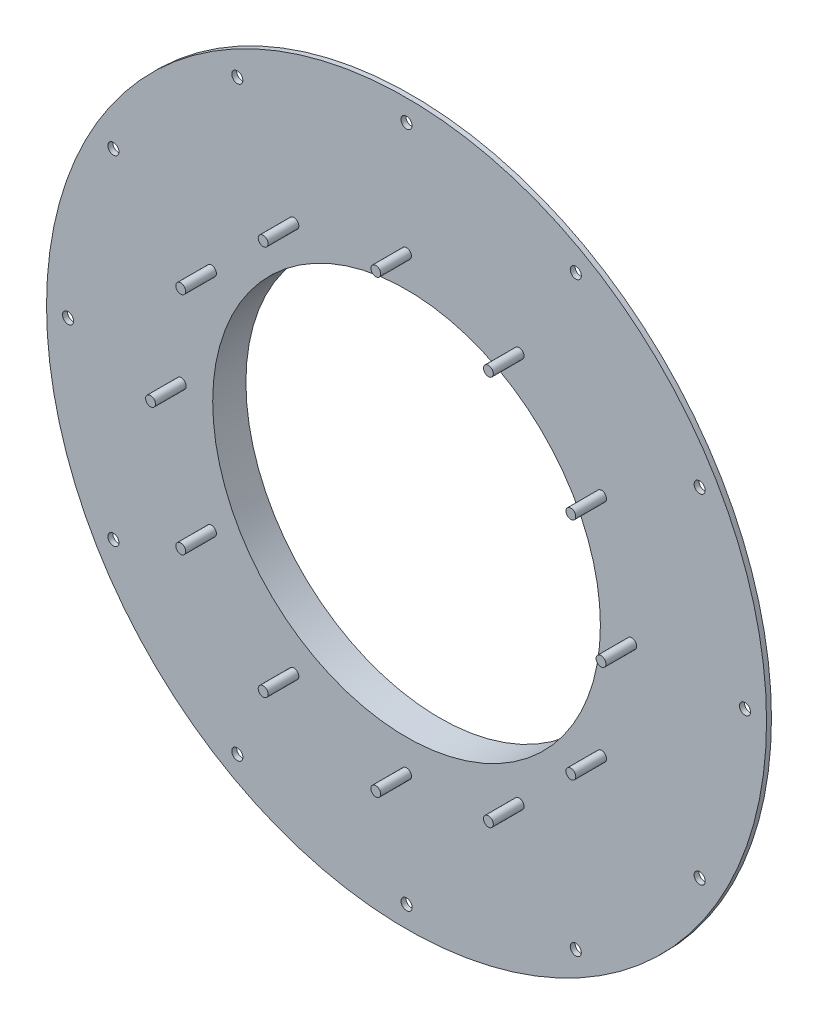
SolidWorks part; units mm, degrees
material "ASTM A36 Steel"
ref_plane "Front Plane" through (0, 0, 0) normal (0, 0, 1) x (1, 0, 0)
ref_plane "Top Plane" through (0, 0, 0) normal (0, 1, 0) x (1, 0, 0)
ref_plane "Right Plane" through (0, 0, 0) normal (1, 0, 0) x (0, 0, -1)
sketch "Sketch1" plane through (0, 0, 0) normal (0, 0, 1) x (1, 0, 0)
  circle A0 centre (0, 0) radius 292.5
  circle A1 centre (0, 0) radius 157.5
  dimension "D1" = 585
  dimension "D2" = 315
extrude "Boss-Extrude1" add sketch "Sketch1" along normal blind 4
sketch "Sketch2" plane through (0, 0, 4) normal (0, 0, 1) x (1, 0, 0)
  circle A0 centre (0, 275) radius 4.5
  dimension "D1" = 9
  dimension "D2" = 275
extrude "Cut-Extrude1" cut sketch "Sketch2" against normal through all
pattern_circular "CirPattern1" count 12 every 30 about axis through (0, 0, 0) along (0, 0, 1) of "Cut-Extrude1"
sketch "Sketch3" plane through (0, 0, 4) normal (0, 0, 1) x (1, 0, 0)
  circle A0 centre (0, 183) radius 4
  dimension "D1" = 8
  dimension "D2" = 183
extrude "Boss-Extrude2" add sketch "Sketch3" along normal blind 25
pattern_circular "CirPattern2" count 12 every 30 about axis through (0, 0, 0) along (0, 0, 1) of "Boss-Extrude2"
sketch "Sketch4" plane through (0, 0, 0) normal (0, 0, -1) x (-1, 0, 0)
  circle A0 centre (0, 0) radius 157.5
extrude "Extrude-Thin1" add sketch "Sketch4" along normal blind 23 thin
